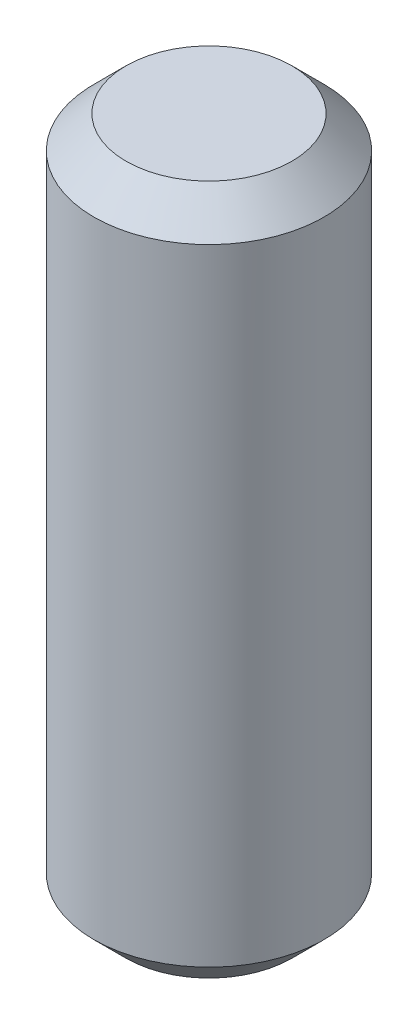
SolidWorks part; units mm, degrees
ref_plane "Front Plane" through (0, 0, 0) normal (0, 0, 1) x (1, 0, 0)
ref_plane "Top Plane" through (0, 0, 0) normal (0, 1, 0) x (1, 0, 0)
ref_plane "Right Plane" through (0, 0, 0) normal (1, 0, 0) x (0, 0, -1)
sketch "Sketch1" plane through (0, 0, 0) normal (0, 1, 0) x (1, 0, 0)
  circle A0 centre (0, 0) radius 2.6
  dimension "D1" = 5.2
extrude "Boss-Extrude1" add sketch "Sketch1" along normal blind 15
chamfer "Chamfer1" distance 0.8 2 edges at (0, 0, 2.6) (0, 15, 2.6)
sketch "Sketch2" plane through (0, 15, 0) normal (0, 1, 0) x (1, 0, 0)
  circle A0 centre (0, 0) radius 2.5
  circle A1 centre (0, 0) radius 2.6
  dimension "D1" = 0.1
extrude "Cut-Extrude2" cut sketch "Sketch2" against normal through all
